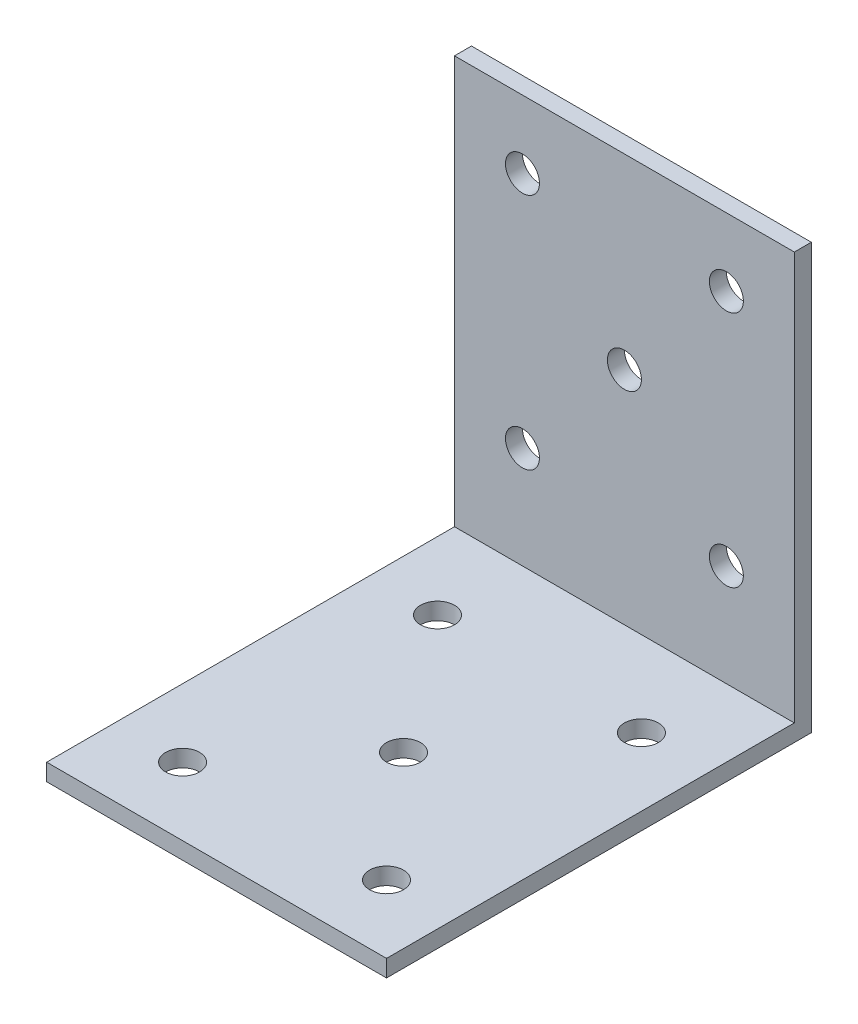
SolidWorks part; units mm, degrees
material "Plastique personnalisé"
ref_plane "Plan de face" through (0, 0, 0) normal (0, 0, 1) x (1, 0, 0)
ref_plane "Plan de dessus" through (0, 0, 0) normal (0, 1, 0) x (1, 0, 0)
ref_plane "Plan de droite" through (0, 0, 0) normal (1, 0, 0) x (0, 0, -1)
sketch "Esquisse1" plane through (0, 0, 0) normal (0, 1, 0) x (1, 0, 0)
  line L1 (-20, 28) -> (20, 28)
  line L2 (-20, 28) -> (-20, -22)
  line L3 (-20, -22) -> (20, -22)
  line L4 (20, 28) -> (20, -22)
  circle A0 centre (0, 0) radius 2
  circle A1 centre (-12, -14) radius 2
  circle A2 centre (-12, 16) radius 2
  circle A3 centre (12, 16) radius 2
  circle A4 centre (12, -14) radius 2
  point P6 (-20, 26)
  dimension "D2" = 4
  dimension "D7" = 4
  dimension "D11" = 8
  dimension "D1" = 50
  dimension "D3" = 20
  dimension "D4" = 22
  dimension "D5" = 40
  dimension "D6" = 8
  dimension "D8" = 8
  dimension "D12" = 8
  dimension "D13" = 12
  dimension "D9" = 2
  dimension "D10" = 2
extrude "Boss.-Extru.1" add sketch "Esquisse1" along normal blind 2
sketch "Esquisse4" plane through (0, 0, -28) normal (0, 0, -1) x (-1, 0, 0)
  line L1 (20, 0) -> (-20, 0)
  line L2 (20, 0) -> (20, 50)
  line L3 (20, 50) -> (-20, 50)
  line L4 (-20, 0) -> (-20, 50)
  line L7 (-20, 2) -> (20, 2) construction
  circle A0 centre (0, 28) radius 2
  circle A1 centre (12, 42) radius 2
  circle A2 centre (-12, 42) radius 2
  circle A3 centre (-12, 14) radius 2
  circle A4 centre (12, 14) radius 2
  point P10 (-10.6112, 42.5)
  point P11 (1.1483, 25.7993)
  dimension "D2" = 4
  dimension "D3" = 4
  dimension "D14" = 14
  dimension "D1" = 50
  dimension "D4" = 8
  dimension "D5" = 8
  dimension "D8" = 8
  dimension "D9" = 22
  dimension "D10" = 20
  dimension "D11" = 8
  dimension "D12" = 12
  dimension "D13" = 14
  dimension "D6" = 2
  dimension "D7" = 2
extrude "Boss.-Extru.3" add sketch "Esquisse4" against normal blind 2
